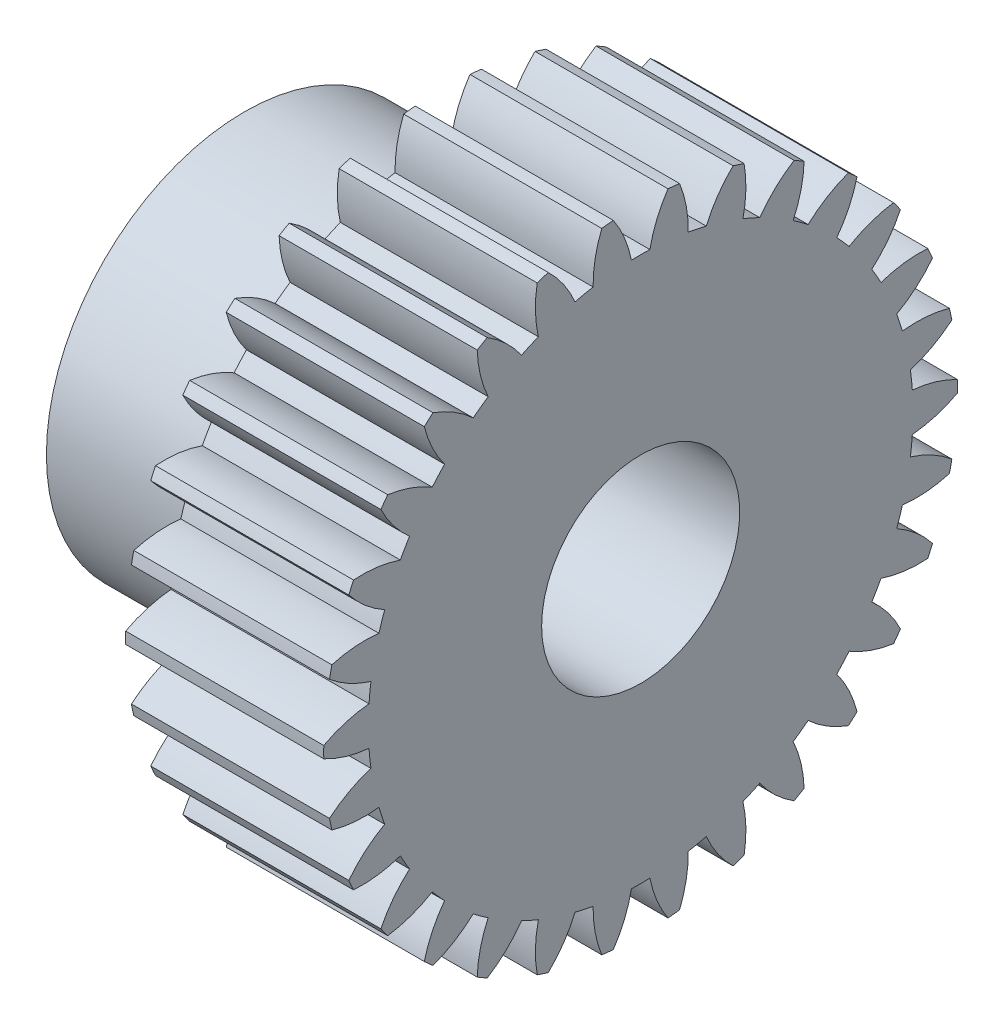
SolidWorks part; units mm, degrees
ref_plane "Plane1" through (0, 0, 0) normal (0, 0, 1) x (1, 0, 0)
ref_plane "Plane2" through (0, 0, 0) normal (0, 1, 0) x (1, 0, 0)
ref_plane "Plane3" through (0, 0, 0) normal (1, 0, 0) x (0, 0, -1)
other "Configuration Table"
sketch "HoldingSke" plane through (0, 0, 0) normal (0, 1, 0) x (1, 0, 0)
  line L0 (0, 0) -> (1.7321, -1)
  line L1 (-15, 0) -> (100, 0) construction
  line L2 (0, 0) -> (-2.1039, 2.3779)
  line L3 (0, 0) -> (-11.863, 4.5341)
  line L4 (0, 0) -> (7.479, 4.318)
  line L5 (0, 0) -> (-9.3695, -3.4946)
  line L6 (0, 0) -> (-4.1448, -2.7965)
  line L7 (-2.1039, 2.3779) -> (0.0486, 12.1435)
  line L8 (-76.2, 54.61) -> (-75.3, 54.61)
  line L9 (-71.009, 38.7566) -> (-53.1078, 45.2721)
  line L10 (-76.2, 71.12) -> (104.1128, 71.12)
  line L11 (0, 0) -> (-5, 0)
  line L12 (-76.2, 101.6) -> (-76.181, 101.6)
  line L13 (24.9733, 27.94) -> (52.9518, 28.4284)
  line L14 (24.9733, 27.94) -> (24.9743, 27.94)
  line L15 (24.9733, 27.94) -> (100.4006, 29.5858)
  line L16 (-63.627, -0.5) -> (-12.827, -0.5)
  circle A0 centre (0, 0) radius 2.5
  circle A1 centre (0, 0) radius 5
  circle A2 centre (0, 0) radius 5
  circle A3 centre (0, 0) radius 2.5
  dimension "MHD" = 10
  dimension "Hub_dia" = 10
  dimension "Bore" = 5
  dimension "MBD" = 5
  dimension "Num_teeth" = 30
  dimension "Pitch" = 2
  dimension "Overall_len" = 10
  dimension "Show_teeth" = 30
  dimension "Thickness" = 5
  dimension "OAL" = 10.0001
  dimension "T_dim" = 0.9
  dimension "Ap" = 20
  dimension "H" = 19.05
  dimension "Pitch_radius" = 180.3128
  dimension "Width" = 5
  dimension "Backlash" = 0.019
  dimension "Addendum_fac" = 1
  dimension "Dedendum_fac" = 1.25
  dimension "Clearance_fac" = 0.25
  dimension "Dedendum_add" = 0.001
  dimension "Module" = 0.5
sketch "BasProSke" plane through (0, 0, 0) normal (0, 1, 0) x (1, 0, 0)
  line L0 (-10, 0) -> (60, 0) construction
  line L1 (0, 0) -> (0, 8)
  line L2 (0, 0) -> (5, 0)
  line L3 (5, 0) -> (5, 8)
  line L4 (5, 8) -> (0, 8)
  dimension "Thickness" = 5
  dimension "Diameter" = 16
revolve "Base-Revolve" add sketch "BasProSke" angle 360 about L0
sketch "TooCutSke" plane through (0, 0, 0) normal (1, 0, 0) x (0, 0, -1)
  line L1 (0, 0) -> (0, 107) construction
  line L2 (0, 0) -> (-0.4258, 7.4879) construction
  line L3 (0, 0) -> (-1.5661, 14.9007) construction
  line L4 (-0.4258, 7.4879) -> (-0.7831, 7.4504) construction
  arc A0 (0.2331, 6.87) -> (-0.2331, 6.87) centre (0, 0) ccw
  arc A1 (0.707, 7.9942) -> (-0.707, 7.9942) centre (0, 0) ccw
  circle A2 centre (0, 0) radius 7.5 construction
  circle A3 centre (0, 0) radius 7.0477 construction
  arc A4 (-0.2331, 6.87) -> (-0.707, 7.9942) centre (-3.1767, 6.2911) ccw
  arc A5 (0.707, 7.9942) -> (0.2331, 6.87) centre (3.1767, 6.2911) ccw
  dimension "Root_dia" = 13.748
  dimension "Overcut_dia" = 16.0508
  dimension "Pitch_dia" = 15
  dimension "Base_dia" = 14.0954
  dimension "Flank_rad" = 3
  dimension "Half_ang" = 6
  dimension "Half_CT" = 0.3593
extrude "ToothCut" cut sketch "TooCutSke" along normal through all
fillet "Breaks" [suppressed] radius 0.01
fillet "RootFillets" [suppressed] radius 0.126
pattern_circular "TeethCuts" count 30 every 12 about axis through (-10, 0, 0) along (1, 0, 0) of "ToothCut", "RootFillets", "Breaks"
sketch "HubNeaOneSke" plane through (0, 0, 0) normal (-1, 0, 0) x (0, 0, 1)
  circle A0 centre (0, 0) radius 5
  dimension "Diameter" = 10
extrude "HubNearOne" add sketch "HubNeaOneSke" along normal blind 5.0001
sketch "HubNeaBotSke" plane through (0, 0, 0) normal (-1, 0, 0) x (0, 0, 1)
  circle A0 centre (0, 0) radius 5
  dimension "Diameter" = 10
extrude "HubNearBoth" [suppressed] add sketch "HubNeaBotSke" along normal blind 2.5
ref_plane "FarPln" through (5, 0, 0) normal (1, 0, 0) x (0, 0, -1)
sketch "HubFarSke" plane through (5, 0, 0) normal (1, 0, 0) x (0, 0, -1)
  circle A0 centre (0, 0) radius 5
  dimension "Diameter" = 10
extrude "HubFar" [suppressed] add sketch "HubFarSke" along normal blind 2.5
sketch "BorSke" plane through (0, 0, 0) normal (1, 0, 0) x (0, 0, -1)
  circle A0 centre (0, 0) radius 2.5
  dimension "Diameter" = 5
extrude "Bore" cut sketch "BorSke" along normal mid plane 20.0001
sketch "KeySke" plane through (0, 0, 0) normal (1, 0, 0) x (0, 0, -1)
  line L0 (-1, 0) -> (-1, 3.4)
  line L1 (-1, 3.4) -> (1, 3.4)
  line L2 (1, 3.4) -> (1, 0)
  line L3 (0, 0) -> (0, 34) construction
  line L4 (-1, 0) -> (1, 0)
  dimension "Offset" = 3.4
  dimension "Width" = 2
extrude "Keyway" [suppressed] cut sketch "KeySke" along normal mid plane 20.0001
pattern_circular "Keyway2" [suppressed] count 2 every 90 about axis through (-10, 0, 0) along (1, 0, 0)
equation "' \"Module@HoldingSke\" = 6.35"
equation "' \"Num_teeth@HoldingSke\" = 12"
equation "' \"Ap@HoldingSke\" =  20"
equation "' \"Ap@HoldingSke\" = 20"
equation "' \"Width@HoldingSke\" = 0.5 * 25.4"
equation "' \"Hub_dia@HoldingSke\"= 1 * 25.4"
equation "' \"Hub_dia@HoldingSke\" = 1 * 25.4"
equation "' \"Overall_len@HoldingSke\" = 1.0 * 25.4"
equation "' \"Bore@HoldingSke\" = 0.75 * 25.4"
equation "' \"T_dim@HoldingSke\" = 0.1 * 25.4"
equation "' \"Width@KeySke\" = 0.25 * 25.4"
equation "' \"Show_teeth@HoldingSke\" = 13"
equation "' \"Backlash@HoldingSke\" = 0.009 * 25.4"
equation "' \"Addendum_fac@HoldingSke\" = 1.0"
equation "' \"Dedendum_fac@HoldingSke\" = 1.25"
equation "' \"Dedendum_add@HoldingSke\" = 0.00005 * 25.4"
equation "' \"Clearance_fac@HoldingSke\" = 0.25"
equation "\"Pitch@HoldingSke\" = 1 / \"Module@HoldingSke\""
equation "\"Overcut_dia@TooCutSke\" = (\"Num_teeth@HoldingSke\" + 2 * \"Addendum_fac@HoldingSke\") / \"Pitch@HoldingSke\" + 0.002 * 25.4"
equation "\"Pitch_dia@TooCutSke\" = \"Num_teeth@HoldingSke\" / \"Pitch@HoldingSke\""
equation "\"Base_dia@TooCutSke\" = \"Num_teeth@HoldingSke\" / \"Pitch@HoldingSke\" * cos((\"Ap@HoldingSke\"  * 3.14159265 / 180))"
equation "\"Root_dia@TooCutSke\" = (\"Num_teeth@HoldingSke\" + 2) / \"Pitch@HoldingSke\" - 2 * (\"Addendum_fac@HoldingSke\" + \"Dedendum_fac@HoldingSke\") / \"Pitch@HoldingSke\" - \"Dedendum_add@HoldingSke\" * 2"
equation "\"Half_ang@TooCutSke\" = 180 / \"Num_teeth@HoldingSke\""
equation "\"Half_CT@TooCutSke\" = \"Num_teeth@HoldingSke\" / \"Pitch@HoldingSke\" * sin((3.14159265 / 2 / \"Num_teeth@HoldingSke\")) / 2 - 7 * \"Backlash@HoldingSke\" / 4"
equation "\"Flank_rad@TooCutSke\" = \"Num_teeth@HoldingSke\" / \"Pitch@HoldingSke\" / 5"
equation "\"Radius@RootFillets\" = \"Clearance_fac@HoldingSke\" / \"Pitch@HoldingSke\" + \"Dedendum_add@HoldingSke\""
equation "\"Break_rad@Breaks\" = 0.02 / \"Pitch@HoldingSke\""
equation "\"Thickness@HoldingSke\" = \"Width@HoldingSke\""
equation "\"OAL@HoldingSke\" = \"Thickness@HoldingSke\""
equation "\"MHD@HoldingSke\" = (\"Num_teeth@HoldingSke\" + 2) / \"Pitch@HoldingSke\" - 2 * (\"Addendum_fac@HoldingSke\" + \"Dedendum_fac@HoldingSke\")  / \"Pitch@HoldingSke\" - \"Dedendum_add@HoldingSke\" * 2"
equation "\"MBD@HoldingSke\" = (\"Num_teeth@HoldingSke\" + 2) / \"Pitch@HoldingSke\" - 2 * (\"Addendum_fac@HoldingSke\" + \"Dedendum_fac@HoldingSke\")  / \"Pitch@HoldingSke\" - \"Dedendum_add@HoldingSke\" * 2 - 0.002 * 25.4"
equation "\"MHD@HoldingSke\" = ((sgn( \"MHD@HoldingSke\" - \"Hub_dia@HoldingSke\" )-1)*( \"MHD@HoldingSke\" - \"Hub_dia@HoldingSke\" ))/-2+ \"Hub_dia@HoldingSke\""
equation "\"MBD@HoldingSke\" = ((sgn( \"MBD@HoldingSke\" - \"Bore@HoldingSke\" )-1)*( \"MBD@HoldingSke\" - \"Bore@HoldingSke\" ))/-2+ \"Bore@HoldingSke\""
equation "\"OAL@HoldingSke\" = ((sgn( \"OAL@HoldingSke\" - \"Overall_len@HoldingSke\" )+1)*( \"OAL@HoldingSke\" - \"Overall_len@HoldingSke\" ))/2 + \"Overall_len@HoldingSke\" + 0.000002 * 25.4"
equation "\"Num_teeth@TeethCuts\" = int( \"Show_teeth@HoldingSke\" ) + 1"
equation "\"Num_teeth@TeethCuts\" = ((sgn( \"Num_teeth@TeethCuts\" - \"Num_teeth@HoldingSke\" )-1)*( \"Num_teeth@TeethCuts\" - \"Num_teeth@HoldingSke\" ))/-2+ \"Num_teeth@HoldingSke\""
equation "\"Num_teeth@TeethCuts\" = ((sgn( \"Num_teeth@TeethCuts\" - 2.0)+1)*( \"Num_teeth@TeethCuts\" - 2.0))/2 +2.0"
equation "\"Angle@TeethCuts\" = 360.0 / \"Num_teeth@HoldingSke\""
equation "\"Diameter@BasProSke\" = (\"Num_teeth@HoldingSke\" + 2 * \"Addendum_fac@HoldingSke\") / \"Pitch@HoldingSke\""
equation "\"Thickness@BasProSke\"  = \"Thickness@HoldingSke\""
equation "' \"Fillet_rad@BasProSke\" =  \"Thickness@HoldingSke\" * 0.05"
equation "' \"Fillet_rad@BasProSke\" = \"Thickness@HoldingSke\" * 0.05"
equation "\"MHD@HoldingSke\" = ((sgn( \"MHD@HoldingSke\" - \"Root_dia@TooCutSke\" )-1)*( \"MHD@HoldingSke\" - \"Root_dia@TooCutSke\" ))/-2+ \"Root_dia@TooCutSke\""
equation "\"Diameter@HubNeaOneSke\" = \"MHD@HoldingSke\""
equation "\"Length@HubNearOne\" = \"OAL@HoldingSke\" - \"Thickness@BasProSke\""
equation "\"Diameter@HubNeaBotSke\" = \"MHD@HoldingSke\""
equation "\"Length@HubNearBoth\" = ( \"OAL@HoldingSke\" - \"Thickness@BasProSke\" ) / 2.0"
equation "\"Thickness@FarPln\" = \"Thickness@BasProSke\""
equation "\"Diameter@HubFarSke\" = \"MHD@HoldingSke\""
equation "\"Length@HubFar\" = ( \"OAL@HoldingSke\" - \"Thickness@BasProSke\" ) / 2.0"
equation "\"Diameter@BorSke\" = \"MBD@HoldingSke\""
equation "\"D1@Bore\" = \"OAL@HoldingSke\" * 2.0"
equation "\"D1@Keyway\" = \"OAL@HoldingSke\" * 2.0"
equation "\"Offset@KeySke\" = \"T_dim@HoldingSke\" + \"MBD@HoldingSke\" / 2.0"
